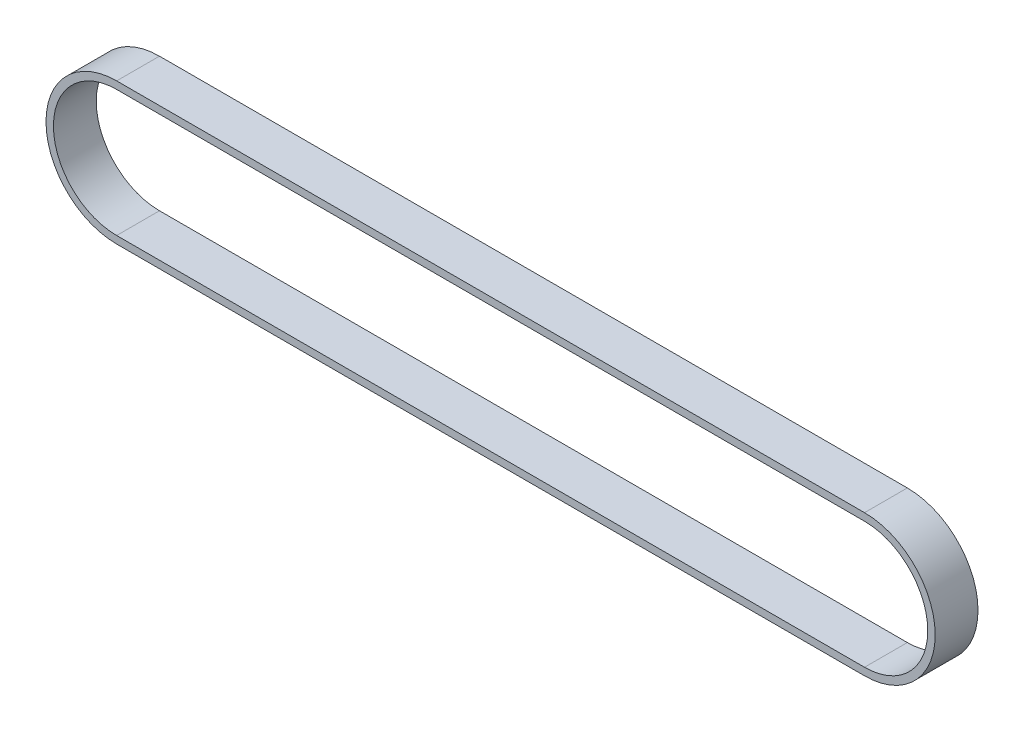
SolidWorks part; units mm, degrees
ref_plane "Front Plane" through (0, 0, 0) normal (0, 0, 1) x (1, 0, 0)
ref_plane "Top Plane" through (0, 0, 0) normal (0, 1, 0) x (1, 0, 0)
ref_plane "Right Plane" through (0, 0, 0) normal (1, 0, 0) x (0, 0, -1)
sketch "Sketch1" plane through (0, 0, 0) normal (0, 0, 1) x (1, 0, 0)
  line L3 (0, 10.56) -> (111.77, 10.56)
  line L4 (0, -10.56) -> (111.77, -10.56)
  arc A5 (0, 10.56) -> (0, -10.56) centre (0, 0) ccw
  arc A6 (111.77, -10.56) -> (111.77, 10.56) centre (111.77, 0) ccw
  point P4 (0, 0)
  point P6 (0, 0)
  point P8 (0, 0)
  point P9 (0, 0)
  point P10 (0, 0)
  point P11 (0, 0)
  point P12 (0, 0)
  point P13 (0, 0)
  point P14 (0, 0)
  point P15 (0, 0)
  point P16 (0, 0)
extrude "Boss-Extrude1" add sketch "Sketch1" along normal blind 6.4
sketch "Sketch2" plane through (0, 0, 6.4) normal (0, 0, 1) x (1, 0, 0)
  line L4 (0, 9.45) -> (111.77, 9.45)
  line L5 (0, -9.45) -> (111.77, -9.45)
  arc A4 (0, 9.45) -> (0, -9.45) centre (0, 0) ccw
  arc A5 (111.77, -9.45) -> (111.77, 9.45) centre (111.77, 0) ccw
  point P4 (0, 0)
  point P9 (0, 0)
extrude "Cut-Extrude1" cut sketch "Sketch2" against normal through all
